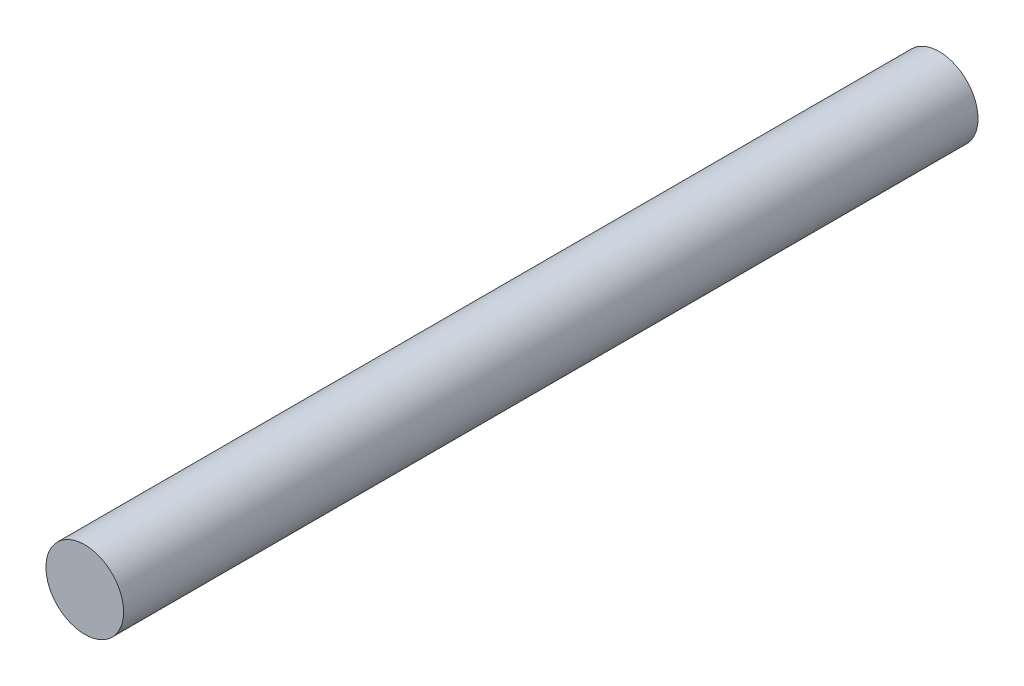
SolidWorks part; units mm, degrees
ref_plane "Front Plane" through (0, 0, 0) normal (0, 0, 1) x (1, 0, 0)
ref_plane "Top Plane" through (0, 0, 0) normal (0, 1, 0) x (1, 0, 0)
ref_plane "Right Plane" through (0, 0, 0) normal (1, 0, 0) x (0, 0, -1)
sketch "Sketch1" plane through (0, 0, 0) normal (0, 0, 1) x (1, 0, 0)
  circle A0 centre (0, 0) radius 4
  dimension "D1" = 8
extrude "Boss-Extrude1" add sketch "Sketch1" along normal blind 88
